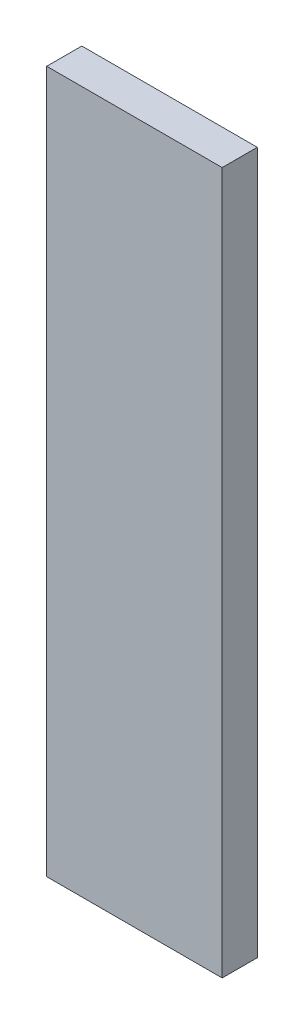
SolidWorks part; units mm, degrees
ref_plane "Plano frontal" through (0, 0, 0) normal (0, 0, 1) x (1, 0, 0)
ref_plane "Plano superior" through (0, 0, 0) normal (0, 1, 0) x (1, 0, 0)
ref_plane "Plano direito" through (0, 0, 0) normal (1, 0, 0) x (0, 0, -1)
sketch "Esboço1" plane through (0, 0, 0) normal (0, 0, 1) x (1, 0, 0)
  line L1 (0, 0) -> (30, 0)
  line L2 (0, 0) -> (0, 120)
  line L3 (0, 120) -> (30, 120)
  line L4 (30, 0) -> (30, 120)
  dimension "D1" = 30
  dimension "D2" = 120
extrude "Ressalto-extrusão1" add sketch "Esboço1" along normal blind 6
